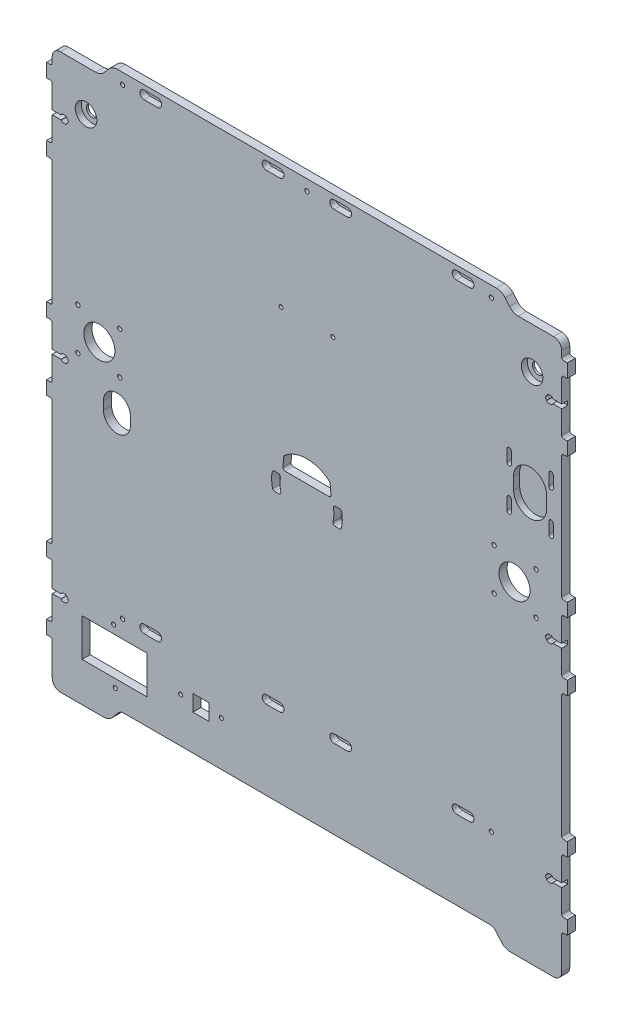
SolidWorks part; units mm, degrees
ref_plane "Alzado" through (0, 0, 0) normal (0, 0, 1) x (1, 0, 0)
ref_plane "Planta" through (0, 0, 0) normal (0, 1, 0) x (1, 0, 0)
ref_plane "Vista lateral" through (0, 0, 0) normal (1, 0, 0) x (0, 0, -1)
sketch "Croquis1" plane through (0, 0, 0) normal (0, 0, 1) x (1, 0, 0)
  line L0 (-10.6795, 26.7767) -> (-13.879, 26.7767)
  line L1 (-34.6047, 239.0104) -> (-34.6047, -170.9896) construction
  line L2 (-13.5151, 39.6941) -> (-10.3636, 39.6941)
  line L3 (-222.9547, 187.3104) -> (-34.6047, 187.3104) construction
  line L4 (-128.7797, 34.0104) -> (-128.7797, 187.3104) construction
  line L5 (-222.9547, 205.7604) -> (-222.9547, 168.8604)
  line L6 (-16.827, 45.3024) -> (-17.4546, 52.4766)
  line L7 (-50.8381, 43.6172) -> (-18.3712, 43.6172)
  line L8 (-51.7547, 52.4766) -> (-52.3823, 45.3024)
  line L9 (-227.1047, 167.3104) -> (-224.5047, 167.3104)
  line L10 (-58.5298, 26.7767) -> (-55.3303, 26.7767)
  line L11 (-55.6942, 39.6941) -> (-58.8457, 39.6941)
  line L12 (-227.1047, 157.3104) -> (-227.1047, 167.3104)
  line L13 (-224.5047, 157.3104) -> (-227.1047, 157.3104)
  line L14 (-224.5047, -89.2896) -> (-227.1047, -89.2896)
  line L15 (-227.1047, -89.2896) -> (-227.1047, -99.2896)
  line L16 (-34.6047, 34.0104) -> (-222.9547, 34.0104) construction
  line L17 (-227.1047, -99.2896) -> (-224.5047, -99.2896)
  line L18 (-18.3712, 43.6172) -> (-50.8381, 43.6172)
  line L19 (-17.4546, 52.4766) -> (-16.827, 45.3024)
  line L20 (-55.3303, 26.7767) -> (-58.5298, 26.7767)
  line L21 (-227.1047, -139.2896) -> (-224.5047, -139.2896)
  line L22 (-227.1047, -149.2896) -> (-227.1047, -139.2896)
  line L23 (-224.5047, -149.2896) -> (-227.1047, -149.2896)
  line L25 (-222.9547, -137.7396) -> (-222.9547, -100.8396)
  line L32 (147.7453, -180.9896) -> (115.7453, -180.9896)
  line L36 (100.8221, -170.9896) -> (-170.0314, -170.9896)
  line L37 (-210.4105, 34.0104) -> (-223.8121, 34.0104) construction
  line L38 (-222.9547, 15.5604) -> (-222.9547, 52.4604)
  line L42 (153.7453, 2.4611) -> (153.7453, -87.7396)
  line L43 (-227.1047, 14.0104) -> (-224.5047, 14.0104)
  line L44 (-227.1047, 4.0104) -> (-227.1047, 14.0104)
  line L45 (-224.5047, 4.0104) -> (-227.1047, 4.0104)
  line L46 (-224.5047, 64.0104) -> (-227.1047, 64.0104)
  line L47 (-227.1047, 64.0104) -> (-227.1047, 54.0104)
  line L48 (-227.1047, 54.0104) -> (-224.5047, 54.0104)
  line L49 (-185.1047, 15.6104) -> (-185.1047, 21.6104)
  line L50 (-165.1047, 21.6104) -> (-165.1047, 15.6104)
  line L51 (-204.0289, 73.6104) -> (-173.0289, 73.6104) construction
  line L52 (-200.9547, -123.9896) -> (-152.9547, -123.9896)
  line L53 (113.2425, 131.6103) -> (113.2419, 140.1103)
  line L54 (116.5488, 140.1105) -> (116.5494, 131.6105)
  line L55 (144.2425, 131.6103) -> (144.2419, 140.1103)
  line L56 (147.5488, 140.1105) -> (147.5494, 131.6105)
  line L57 (130.2626, 109.7644) -> (130.2626, 118.2644) construction
  line L58 (107.5281, 109.7644) -> (107.5281, 118.2644) construction
  line L59 (116.5488, 140.1105) -> (147.5488, 140.1105) construction
  line L60 (113.2425, 100.6103) -> (113.2419, 109.1103)
  line L61 (116.5488, 109.1105) -> (116.5494, 100.6105)
  line L62 (144.2425, 100.6103) -> (144.2419, 109.1103)
  line L63 (-34.6047, 34.0104) -> (153.7453, 34.0104) construction
  line L64 (-200.9547, -123.9896) -> (-200.9547, -151.9896)
  line L65 (-200.9547, -151.9896) -> (-152.9547, -151.9896)
  line L66 (-152.9547, -123.9896) -> (-152.9547, -151.9896)
  line L67 (-118.9547, -132.8214) -> (-106.9547, -132.8214)
  line L68 (-118.9547, -132.8214) -> (-118.9547, -144.8214)
  line L69 (109.234, -177.9533) -> (105.0418, -172.9573)
  line L73 (-222.9547, 155.7604) -> (-222.9547, 65.5604)
  line L74 (-222.9547, 2.4611) -> (-222.9547, -87.7396)
  line L75 (-222.9547, -150.8396) -> (-222.9547, -174.9896)
  line L77 (153.7453, -150.8396) -> (153.7453, -174.9896)
  line L81 (157.8953, -99.2896) -> (155.2953, -99.2896)
  line L82 (157.8953, -89.2896) -> (157.8953, -99.2896)
  line L83 (155.2953, -89.2896) -> (157.8953, -89.2896)
  line L84 (155.2953, -149.2896) -> (157.8953, -149.2896)
  line L85 (157.8953, -149.2896) -> (157.8953, -139.2896)
  line L86 (157.8953, -139.2896) -> (155.2953, -139.2896)
  line L87 (153.7453, -137.7396) -> (153.7453, -100.8396)
  line L91 (155.2953, 4.0104) -> (157.8953, 4.0104)
  line L92 (157.8953, 4.0104) -> (157.8953, 14.0104)
  line L93 (157.8953, 14.0104) -> (155.2953, 14.0104)
  line L94 (-118.9547, -144.8214) -> (-106.9547, -144.8214)
  line L95 (-106.9547, -132.8214) -> (-106.9547, -144.8214)
  line L96 (-118.9547, -132.8214) -> (-106.9547, -144.8214) construction
  line L97 (-118.9547, -144.8214) -> (-106.9547, -132.8214) construction
  line L98 (-204.0289, 73.6104) -> (-204.0289, 42.6104) construction
  line L99 (134.8196, 73.6104) -> (134.8196, 42.6104) construction
  line L100 (134.8196, 73.6104) -> (103.8196, 73.6104) construction
  line L101 (118.8953, 57.6104) -> (118.8953, 118.2644) construction
  line L102 (147.5488, 109.1105) -> (147.5494, 100.6105)
  line L103 (153.7453, 15.5604) -> (153.7453, 52.4604)
  line L104 (157.8953, 54.0104) -> (155.2953, 54.0104)
  line L105 (157.8953, 64.0104) -> (157.8953, 54.0104)
  line L106 (155.2953, 64.0104) -> (157.8953, 64.0104)
  line L107 (153.7453, 155.7604) -> (153.7453, 65.5604)
  line L108 (155.2953, 157.3104) -> (157.8953, 157.3104)
  line L109 (157.8953, 157.3104) -> (157.8953, 167.3104)
  line L110 (157.8953, 167.3104) -> (155.2953, 167.3104)
  line L115 (153.7453, 205.7604) -> (153.7453, 168.8604)
  line L116 (157.8953, 207.3104) -> (155.2953, 207.3104)
  line L117 (157.8953, 217.3104) -> (157.8953, 207.3104)
  line L118 (155.2953, 217.3104) -> (157.8953, 217.3104)
  line L119 (153.7453, 223.1104) -> (153.7453, 218.8604)
  line L120 (121.7453, 229.1104) -> (147.7453, 229.1104)
  line L121 (112.0224, 235.9741) -> (115.234, 232.1467)
  line L131 (105.511, 239.0104) -> (-174.7203, 239.0104)
  line L132 (-181.2317, 235.9741) -> (-184.4433, 232.1467)
  line L133 (-190.9547, 229.1104) -> (-216.9547, 229.1104)
  line L134 (-222.9547, 223.1104) -> (-222.9547, 218.8604)
  line L135 (-224.5047, 217.3104) -> (-227.1047, 217.3104)
  line L136 (-227.1047, 217.3104) -> (-227.1047, 207.3104)
  line L137 (-227.1047, 207.3104) -> (-224.5047, 207.3104)
  line L142 (-216.9547, -180.9896) -> (-184.9547, -180.9896)
  line L143 (-178.4433, -177.9533) -> (-174.2511, -172.9573)
  line L145 (-222.9547, 110.6604) -> (-34.6047, 110.6604) construction
  arc A0 (-8.8356, 38.4045) -> (-9.1714, 27.9685) centre (-34.6047, 34.0104) cw
  arc A1 (-9.1714, 27.9685) -> (-10.6795, 26.7767) centre (-10.6795, 28.3268) cw
  arc A2 (-222.9547, 168.8604) -> (-224.5047, 167.3104) centre (-224.5047, 168.8604) cw
  arc A3 (-224.5047, 157.3104) -> (-222.9547, 155.7604) centre (-224.5047, 155.7604) cw
  arc A4 (-13.879, 26.7767) -> (-15.3739, 28.7367) centre (-13.879, 28.3268) cw
  arc A5 (-15.0363, 37.8458) -> (-15.3739, 28.7367) centre (-34.6047, 34.0104) cw
  arc A6 (-15.0363, 37.8458) -> (-13.5151, 39.6941) centre (-13.5151, 38.144) cw
  arc A7 (-224.5047, -89.2896) -> (-222.9547, -87.7396) centre (-224.5047, -87.7396) ccw
  arc A8 (-222.9547, -100.8396) -> (-224.5047, -99.2896) centre (-224.5047, -100.8396) ccw
  arc A9 (-222.9547, -137.7396) -> (-224.5047, -139.2896) centre (-224.5047, -137.7396) cw
  arc A10 (-18.3712, 43.6172) -> (-16.827, 45.3024) centre (-18.3712, 45.1673) ccw
  arc A11 (-52.3823, 45.3024) -> (-50.8381, 43.6172) centre (-50.8381, 45.1673) ccw
  arc A12 (-51.2153, 53.5218) -> (-51.7547, 52.4766) centre (-50.2105, 52.3415) ccw
  arc A13 (-17.994, 53.5218) -> (-51.2153, 53.5218) centre (-34.6047, 34.0104) ccw
  arc A14 (-17.4546, 52.4766) -> (-17.994, 53.5218) centre (-18.9988, 52.3415) ccw
  arc A15 (-224.5047, -149.2896) -> (-222.9547, -150.8396) centre (-224.5047, -150.8396) cw
  arc A16 (-10.3636, 39.6941) -> (-8.8356, 38.4045) centre (-10.3636, 38.144) cw
  arc A18 (-222.9547, -174.9896) -> (-216.9547, -180.9896) centre (-216.9547, -174.9896) ccw
  arc A22 (-55.3303, 26.7767) -> (-53.8354, 28.7367) centre (-55.3303, 28.3268) ccw
  arc A23 (-60.0379, 27.9685) -> (-58.5298, 26.7767) centre (-58.5298, 28.3268) ccw
  arc A24 (-60.3738, 38.4045) -> (-60.0379, 27.9685) centre (-34.6047, 34.0104) ccw
  arc A25 (-58.8457, 39.6941) -> (-60.3738, 38.4045) centre (-58.8457, 38.144) ccw
  arc A26 (-54.173, 37.8458) -> (-55.6942, 39.6941) centre (-55.6942, 38.144) ccw
  arc A27 (-54.173, 37.8458) -> (-53.8354, 28.7367) centre (-34.6047, 34.0104) ccw
  arc A28 (-222.9547, 15.5604) -> (-224.5047, 14.0104) centre (-224.5047, 15.5604) cw
  arc A29 (-224.5047, 4.0104) -> (-222.9547, 2.4604) centre (-224.5047, 2.4604) cw
  arc A30 (-224.5047, 64.0104) -> (-222.9547, 65.5604) centre (-224.5047, 65.5604) ccw
  arc A31 (-222.9547, 52.4604) -> (-224.5047, 54.0104) centre (-224.5047, 52.4604) ccw
  arc A40 (100.8221, -170.9896) -> (105.0418, -172.9573) centre (100.8221, -176.498) cw
  arc A41 (115.7453, -180.9896) -> (109.234, -177.9533) centre (115.7453, -172.4896) cw
  arc A42 (153.7453, -174.9896) -> (147.7453, -180.9896) centre (147.7453, -174.9896) cw
  arc A45 (153.7453, -100.8396) -> (155.2953, -99.2896) centre (155.2953, -100.8396) cw
  arc A46 (-17.994, 53.5218) -> (-51.2153, 53.5218) centre (-34.6047, 34.0104) ccw
  arc A47 (-17.4546, 52.4766) -> (-17.994, 53.5218) centre (-18.9988, 52.3415) ccw
  arc A48 (-18.3712, 43.6172) -> (-16.827, 45.3024) centre (-18.3712, 45.1673) ccw
  arc A49 (-52.3823, 45.3024) -> (-50.8381, 43.6172) centre (-50.8381, 45.1673) ccw
  arc A50 (-51.2153, 53.5218) -> (-51.7547, 52.4766) centre (-50.2105, 52.3415) ccw
  arc A51 (-58.8457, 39.6941) -> (-60.3738, 38.4045) centre (-58.8457, 38.144) ccw
  arc A52 (-60.3738, 38.4045) -> (-60.0379, 27.9685) centre (-34.6047, 34.0104) ccw
  arc A53 (-60.0379, 27.9685) -> (-58.5298, 26.7767) centre (-58.5298, 28.3268) ccw
  arc A54 (-55.3303, 26.7767) -> (-53.8354, 28.7367) centre (-55.3303, 28.3268) ccw
  arc A55 (-54.173, 37.8458) -> (-53.8354, 28.7367) centre (-34.6047, 34.0104) ccw
  arc A56 (-54.173, 37.8458) -> (-55.6942, 39.6941) centre (-55.6942, 38.144) ccw
  arc A62 (155.2953, -89.2896) -> (153.7453, -87.7396) centre (155.2953, -87.7396) cw
  arc A63 (155.2953, -149.2896) -> (153.7453, -150.8396) centre (155.2953, -150.8396) ccw
  arc A64 (153.7453, -137.7396) -> (155.2953, -139.2896) centre (155.2953, -137.7396) ccw
  arc A68 (155.2953, 4.0104) -> (153.7453, 2.4604) centre (155.2953, 2.4604) ccw
  arc A69 (153.7453, 15.5604) -> (155.2953, 14.0104) centre (155.2953, 15.5604) ccw
  circle A70 centre (101.7453, 231.0104) radius 1.6
  circle A71 centre (-34.6047, 231.0104) radius 1.6
  circle A73 centre (101.7453, -110.9896) radius 1.6
  circle A74 centre (-177.5547, -117.9896) radius 1.5
  arc A75 (153.7453, 52.4604) -> (155.2953, 54.0104) centre (155.2953, 52.4604) cw
  arc A76 (155.2953, 64.0104) -> (153.7453, 65.5604) centre (155.2953, 65.5604) cw
  arc A77 (155.2953, 157.3104) -> (153.7453, 155.7604) centre (155.2953, 155.7604) ccw
  arc A78 (153.7453, 168.8604) -> (155.2953, 167.3104) centre (155.2953, 168.8604) ccw
  arc A83 (153.7453, 205.7604) -> (155.2953, 207.3104) centre (155.2953, 205.7604) cw
  arc A84 (155.2953, 217.3104) -> (153.7453, 218.8604) centre (155.2953, 218.8604) cw
  arc A85 (147.7453, 229.1104) -> (153.7453, 223.1104) centre (147.7453, 223.1104) cw
  arc A86 (121.7453, 229.1104) -> (115.234, 232.1467) centre (121.7453, 237.6104) cw
  arc A87 (105.511, 239.0104) -> (112.0224, 235.9741) centre (105.511, 230.5104) cw
  circle A88 centre (-176.3547, -157.9896) radius 1.5
  arc A89 (-174.7203, 239.0104) -> (-181.2317, 235.9741) centre (-174.7203, 230.5104) ccw
  arc A90 (-190.9547, 229.1104) -> (-184.4433, 232.1467) centre (-190.9547, 237.6104) ccw
  arc A91 (-216.9547, 229.1104) -> (-222.9547, 223.1104) centre (-216.9547, 223.1104) ccw
  arc A92 (-224.5047, 217.3104) -> (-222.9547, 218.8604) centre (-224.5047, 218.8604) ccw
  arc A93 (-222.9547, 205.7604) -> (-224.5047, 207.3104) centre (-224.5047, 205.7604) ccw
  arc A97 (-184.9547, -180.9896) -> (-178.4433, -177.9533) centre (-184.9547, -172.4896) ccw
  arc A98 (-170.0314, -170.9896) -> (-174.2511, -172.9573) centre (-170.0314, -176.498) ccw
  circle A99 centre (-188.1047, 57.6104) radius 11.5
  circle A100 centre (-204.0289, 73.6104) radius 1.6
  circle A101 centre (-173.0289, 73.6104) radius 1.6
  circle A102 centre (-204.0289, 42.6104) radius 1.6
  circle A103 centre (-173.0289, 42.6104) radius 1.6
  arc A104 (-165.1047, 21.6104) -> (-185.1047, 21.6104) centre (-175.1047, 21.6104) ccw
  arc A105 (-185.1047, 15.6104) -> (-165.1047, 15.6104) centre (-175.1047, 15.6104) ccw
  circle A106 centre (-127.9547, -137.9896) radius 1.5
  circle A107 centre (-197.9547, 198.6104) radius 4.25
  circle A108 centre (-170.9547, 231.0104) radius 1.6
  circle A109 centre (-97.9547, -137.9896) radius 1.5
  circle A110 centre (103.8196, 42.6104) radius 1.6
  circle A111 centre (134.8196, 42.6104) radius 1.6
  circle A112 centre (103.8196, 73.6104) radius 1.6
  circle A113 centre (131.8953, 198.6104) radius 4.25
  arc A114 (116.5488, 140.1105) -> (113.2419, 140.1103) centre (114.8953, 140.1104) ccw
  arc A115 (113.2425, 131.6103) -> (116.5494, 131.6105) centre (114.8959, 131.6104) ccw
  arc A116 (147.5488, 140.1105) -> (144.2419, 140.1103) centre (145.8953, 140.1104) ccw
  arc A117 (144.2425, 131.6103) -> (147.5494, 131.6105) centre (145.8959, 131.6104) ccw
  arc A118 (130.2626, 118.2644) -> (107.5281, 118.2644) centre (118.8953, 118.2644) ccw construction
  arc A119 (107.5281, 109.7644) -> (130.2626, 109.7644) centre (118.8953, 109.7644) ccw construction
  arc A120 (116.5488, 109.1105) -> (113.2419, 109.1103) centre (114.8953, 109.1104) ccw
  arc A121 (113.2425, 100.6103) -> (116.5494, 100.6105) centre (114.8959, 100.6104) ccw
  arc A122 (147.5488, 109.1105) -> (144.2419, 109.1103) centre (145.8953, 109.1104) ccw
  arc A123 (144.2425, 100.6103) -> (147.5494, 100.6105) centre (145.8959, 100.6104) ccw
  circle A124 centre (134.8196, 73.6104) radius 1.6
  circle A125 centre (118.8953, 57.6104) radius 11.5
  circle A133 centre (-170.9547, -110.9896) radius 1.6
  point P250 (-112.9547, -138.8214)
  dimension "D1" = 8.5
  dimension "D3" = 8.5
  dimension "D4" = 6
  dimension "D8" = 1.55
  dimension "D11" = 1.55
  dimension "D12" = 25
  dimension "D14" = 8.5
  dimension "D15" = 25.6244
  dimension "D21" = 6
  dimension "D23" = 40
  dimension "D26" = 8
  dimension "D27" = 32
  dimension "D29" = 3.2
  dimension "D30" = 8.5
  dimension "D7" = 3.2
  dimension "D31" = 48
  dimension "D38" = 6
  dimension "D39" = 6
  dimension "D40" = 25
  dimension "D45" = 9
  dimension "D47" = 3.2
  dimension "D54" = 23
  dimension "D57" = 10
  dimension "D58" = 10
  dimension "D63" = 89
  dimension "D64" = 8.5
  dimension "D65" = 1.6534
  dimension "D66" = 1.6534
  dimension "D20" = 1.5501
  dimension "D67" = 1.5501
  dimension "D71" = 1.5501
  dimension "D72" = 1.5501
  dimension "D75" = 1.5501
  dimension "D77" = 1.5501
  dimension "D78" = 26.1411
  dimension "D79" = 1.5501
  dimension "D81" = 1.5501
  dimension "D82" = 19.9407
  dimension "D87" = 1.55
  dimension "D88" = 1.55
  dimension "D2" = 50
  dimension "D5" = 8
  dimension "D6" = 52
  dimension "D9" = 10
  dimension "D10" = 2.6
  dimension "D13" = 40.4
  dimension "D16" = 21.85
  dimension "D17" = 11.8
  dimension "D18" = 32
  dimension "D19" = 15.9
  dimension "D22" = 7.1742
  dimension "D24" = 40.4
  dimension "D25" = 38.85
  dimension "D28" = 52
  dimension "D32" = 10
  dimension "D62" = 7.1682
  dimension "D89" = 22.5
  dimension "D33" = 6.5218
  dimension "D34" = 50
  dimension "D35" = 28
  dimension "D36" = 13
  dimension "D37" = 22
  dimension "D41" = 14
  dimension "D42" = 12
  dimension "D43" = 12
  dimension "D44" = 9
  dimension "D46" = 14
  dimension "D48" = 2
  dimension "D49" = 31
  dimension "D51" = 31
  dimension "D52" = 16
  dimension "D53" = 36
  dimension "D55" = 141
  dimension "D56" = 39
  dimension "D59" = 6
  dimension "D60" = 6
  dimension "D61" = 52
  dimension "D68" = 2
  dimension "D69" = 31
  dimension "D73" = 7.1742
  dimension "D74" = 32.467
  dimension "D76" = 3.1515
  dimension "D80" = 3.1995
  dimension "D83" = 24.2411
  dimension "D84" = 23.9251
  dimension "D85" = 10
  dimension "D86" = 2.6
  dimension "D50" = 2
  dimension "D70" = 2
extrude "Saliente-Extruir1" add sketch "Croquis1" along normal blind 6
sketch "Croquis10" plane through (0, 0, 6) normal (0, 0, 1) x (1, 0, 0)
  line L0 (142.672, 116.1611) -> (142.672, 124.6104)
  line L1 (118.2177, 116.019) -> (118.1195, 124.4678)
  line L2 (114.8953, 140.1104) -> (145.8953, 109.1104) construction
  line L3 (-216.4544, 188.8604) -> (-222.9547, 188.8604)
  line L4 (-209.8753, 187.3104) -> (-223.8121, 187.3104) construction
  line L5 (-214.9445, 190.0604) -> (-213.3945, 190.0604)
  line L6 (-211.8813, 188.8465) -> (-211.8813, 188.6773)
  line L7 (-222.9547, 34.0104) -> (153.7453, 34.0104) construction
  line L8 (-211.8813, 185.9436) -> (-211.8813, 185.7743)
  line L9 (-214.9445, 184.5604) -> (-213.3945, 184.5604)
  line L10 (-222.9547, 188.8604) -> (-222.9547, 185.7604)
  line L11 (-34.6047, 239.0104) -> (-34.6047, -170.9896) construction
  line L12 (105.511, 239.0104) -> (-174.7203, 239.0104) construction
  line L13 (100.8221, -170.9896) -> (-170.0314, -170.9896) construction
  line L14 (-222.9547, 15.5604) -> (-222.9547, 52.4604) construction
  line L15 (-216.4544, 185.7604) -> (-222.9547, 185.7604)
  line L16 (-222.9547, 110.6604) -> (-34.6047, 110.6604) construction
  line L17 (-222.9547, 155.7604) -> (-222.9547, 65.5604) construction
  line L18 (-209.8753, 34.0104) -> (-223.8121, 34.0104) construction
  line L19 (-216.4544, 35.5604) -> (-222.9547, 35.5604)
  line L20 (-222.9547, 32.4604) -> (-222.9547, 35.5604)
  line L21 (-214.9445, 36.7604) -> (-213.3945, 36.7604)
  line L22 (-211.8813, 35.3773) -> (-211.8813, 35.5465)
  line L23 (-211.8813, 32.4743) -> (-211.8813, 32.6436)
  line L24 (-214.9445, 31.2604) -> (-213.3945, 31.2604)
  line L25 (-216.4544, 32.4604) -> (-222.9547, 32.4604)
  line L26 (-209.8753, -119.2896) -> (-223.8121, -119.2896) construction
  line L27 (-216.4544, -117.7396) -> (-222.9547, -117.7396)
  line L28 (-222.9547, -120.8396) -> (-222.9547, -117.7396)
  line L29 (-214.9445, -116.5396) -> (-213.3945, -116.5396)
  line L30 (-211.8813, -117.9227) -> (-211.8813, -117.7535)
  line L31 (-211.8813, -120.8257) -> (-211.8813, -120.6564)
  line L32 (-214.9445, -122.0396) -> (-213.3945, -122.0396)
  line L33 (-216.4544, -120.8396) -> (-222.9547, -120.8396)
  line L34 (140.666, -119.2896) -> (154.6028, -119.2896) construction
  line L35 (147.2451, -120.8396) -> (153.7453, -120.8396)
  line L36 (145.7352, -122.0396) -> (144.1852, -122.0396)
  line L37 (142.672, -120.8257) -> (142.672, -120.6564)
  line L38 (142.672, -117.9227) -> (142.672, -117.7535)
  line L39 (145.7352, -116.5396) -> (144.1852, -116.5396)
  line L40 (153.7453, -120.8396) -> (153.7453, -117.7396)
  line L41 (147.2451, -117.7396) -> (153.7453, -117.7396)
  line L42 (140.666, 34.0104) -> (154.6028, 34.0104) construction
  line L43 (147.2451, 32.4604) -> (153.7453, 32.4604)
  line L44 (145.7352, 31.2604) -> (144.1852, 31.2604)
  line L45 (142.672, 32.4743) -> (142.672, 32.6436)
  line L46 (142.672, 35.3773) -> (142.672, 35.5465)
  line L47 (145.7352, 36.7604) -> (144.1852, 36.7604)
  line L48 (153.7453, 32.4604) -> (153.7453, 35.5604)
  line L49 (147.2451, 35.5604) -> (153.7453, 35.5604)
  line L50 (140.666, 187.3104) -> (154.6028, 187.3104) construction
  line L51 (147.2451, 185.7604) -> (153.7453, 185.7604)
  line L52 (153.7453, 188.8604) -> (153.7453, 185.7604)
  line L53 (145.7352, 184.5604) -> (144.1852, 184.5604)
  line L54 (142.672, 185.9436) -> (142.672, 185.7743)
  line L55 (142.672, 188.8465) -> (142.672, 188.6773)
  line L56 (145.7352, 190.0604) -> (144.1852, 190.0604)
  line L57 (147.2451, 188.8604) -> (153.7453, 188.8604)
  line L58 (-64.6047, 235.6104) -> (-54.6047, 235.6104)
  line L59 (-64.6047, 229.4104) -> (-54.6047, 229.4104)
  line L60 (153.7453, 15.5604) -> (153.7453, 52.4604) construction
  line L61 (-155.1047, 235.6104) -> (-145.1047, 235.6104)
  line L62 (-155.1047, 229.4104) -> (-145.1047, 229.4104)
  line L63 (-54.6047, 229.4104) -> (-145.1047, 229.4104) construction
  line L64 (-4.6047, 229.4104) -> (-14.6047, 229.4104)
  line L65 (-4.6047, 235.6104) -> (-14.6047, 235.6104)
  line L66 (85.8953, 235.6104) -> (75.8953, 235.6104)
  line L67 (85.8953, 229.4104) -> (75.8953, 229.4104)
  line L68 (-64.6047, -112.5896) -> (-54.6047, -112.5896)
  line L69 (-64.6047, -106.3896) -> (-54.6047, -106.3896)
  line L70 (-155.1047, -106.3896) -> (-145.1047, -106.3896)
  line L71 (-155.1047, -112.5896) -> (-145.1047, -112.5896)
  line L72 (-4.6047, -112.5896) -> (-14.6047, -112.5896)
  line L73 (-4.6047, -106.3896) -> (-14.6047, -106.3896)
  line L74 (85.8953, -106.3896) -> (75.8953, -106.3896)
  line L75 (85.8953, -112.5896) -> (75.8953, -112.5896)
  line L76 (-54.6047, 229.4104) -> (-54.6047, -112.5896) construction
  line L77 (145.8953, 140.1104) -> (114.8953, 109.1104) construction
  line L78 (-190.9547, 229.1104) -> (-216.9547, 229.1104) construction
  line L79 (-227.1047, 64.0104) -> (-227.1047, 54.0104) construction
  line L80 (-227.1047, 59.0104) -> (157.8953, 59.0104) construction
  line L81 (157.8953, 64.0104) -> (157.8953, 54.0104) construction
  line L82 (-222.9547, 205.7604) -> (-222.9547, 168.8604) construction
  arc A0 (142.672, 124.6104) -> (118.1195, 124.4678) centre (130.3953, 124.6104) ccw
  arc A1 (118.2177, 116.019) -> (142.672, 116.1611) centre (130.4444, 116.1611) ccw
  arc A2 (-214.9445, 36.7604) -> (-216.4544, 35.5604) centre (-214.9445, 35.2104) ccw
  circle A3 centre (131.8953, 198.6104) radius 4.25
  arc A4 (-211.8813, 32.4743) -> (-213.3945, 31.2604) centre (-213.3945, 32.8104) cw
  arc A5 (-214.9445, 31.2604) -> (-216.4544, 32.4604) centre (-214.9445, 32.8104) cw
  arc A6 (-211.8813, 35.5465) -> (-213.3945, 36.7604) centre (-213.3945, 35.2104) ccw
  arc A7 (-211.8813, 35.3773) -> (-211.8813, 32.6436) centre (-212.6118, 34.0104) cw
  arc A8 (-211.8813, 185.9436) -> (-211.8813, 188.6773) centre (-212.6118, 187.3104) ccw
  arc A9 (-214.9445, -116.5396) -> (-216.4544, -117.7396) centre (-214.9445, -118.0896) ccw
  arc A10 (-211.8813, -120.8257) -> (-213.3945, -122.0396) centre (-213.3945, -120.4896) cw
  arc A11 (-214.9445, -122.0396) -> (-216.4544, -120.8396) centre (-214.9445, -120.4896) cw
  arc A12 (-211.8813, -117.7535) -> (-213.3945, -116.5396) centre (-213.3945, -118.0896) ccw
  arc A13 (-211.8813, -117.9227) -> (-211.8813, -120.6564) centre (-212.6118, -119.2896) cw
  arc A14 (142.672, -117.9227) -> (142.672, -120.6564) centre (143.4025, -119.2896) ccw
  arc A15 (142.672, -117.7535) -> (144.1852, -116.5396) centre (144.1852, -118.0896) cw
  arc A16 (145.7352, -122.0396) -> (147.2451, -120.8396) centre (145.7352, -120.4896) ccw
  arc A17 (142.672, -120.8257) -> (144.1852, -122.0396) centre (144.1852, -120.4896) ccw
  arc A18 (145.7352, -116.5396) -> (147.2451, -117.7396) centre (145.7352, -118.0896) cw
  arc A19 (142.672, 35.3773) -> (142.672, 32.6436) centre (143.4025, 34.0104) ccw
  arc A20 (142.672, 35.5465) -> (144.1852, 36.7604) centre (144.1852, 35.2104) cw
  arc A21 (145.7352, 31.2604) -> (147.2451, 32.4604) centre (145.7352, 32.8104) ccw
  arc A22 (142.672, 32.4743) -> (144.1852, 31.2604) centre (144.1852, 32.8104) ccw
  arc A23 (145.7352, 36.7604) -> (147.2451, 35.5604) centre (145.7352, 35.2104) cw
  arc A24 (145.7352, 184.5604) -> (147.2451, 185.7604) centre (145.7352, 186.1104) ccw
  arc A25 (142.672, 188.8465) -> (144.1852, 190.0604) centre (144.1852, 188.5104) cw
  arc A26 (145.7352, 190.0604) -> (147.2451, 188.8604) centre (145.7352, 188.5104) cw
  arc A27 (142.672, 185.7743) -> (144.1852, 184.5604) centre (144.1852, 186.1104) ccw
  arc A28 (142.672, 185.9436) -> (142.672, 188.6773) centre (143.4025, 187.3104) cw
  arc A29 (-54.6047, 229.4104) -> (-54.6047, 235.6104) centre (-54.6047, 232.5104) ccw
  arc A30 (-64.6047, 235.6104) -> (-64.6047, 229.4104) centre (-64.6047, 232.5104) ccw
  arc A31 (-145.1047, 229.4104) -> (-145.1047, 235.6104) centre (-145.1047, 232.5104) ccw
  arc A32 (-155.1047, 235.6104) -> (-155.1047, 229.4104) centre (-155.1047, 232.5104) ccw
  arc A33 (-14.6047, 229.4104) -> (-14.6047, 235.6104) centre (-14.6047, 232.5104) cw
  arc A34 (-4.6047, 235.6104) -> (-4.6047, 229.4104) centre (-4.6047, 232.5104) cw
  arc A35 (75.8953, 229.4104) -> (75.8953, 235.6104) centre (75.8953, 232.5104) cw
  arc A36 (85.8953, 235.6104) -> (85.8953, 229.4104) centre (85.8953, 232.5104) cw
  arc A37 (-54.6047, -112.5896) -> (-54.6047, -106.3896) centre (-54.6047, -109.4896) ccw
  arc A38 (-64.6047, -106.3896) -> (-64.6047, -112.5896) centre (-64.6047, -109.4896) ccw
  arc A39 (-145.1047, -112.5896) -> (-145.1047, -106.3896) centre (-145.1047, -109.4896) ccw
  arc A40 (-155.1047, -106.3896) -> (-155.1047, -112.5896) centre (-155.1047, -109.4896) ccw
  arc A41 (-14.6047, -112.5896) -> (-14.6047, -106.3896) centre (-14.6047, -109.4896) cw
  arc A42 (-4.6047, -106.3896) -> (-4.6047, -112.5896) centre (-4.6047, -109.4896) cw
  arc A43 (75.8953, -112.5896) -> (75.8953, -106.3896) centre (75.8953, -109.4896) cw
  arc A44 (85.8953, -106.3896) -> (85.8953, -112.5896) centre (85.8953, -109.4896) cw
  circle A45 centre (-197.9547, 198.6104) radius 8
  circle A46 centre (131.8953, 198.6104) radius 8
  circle A47 centre (131.8953, 198.6104) radius 4.25 construction
  arc A63 (-211.8813, 185.7743) -> (-213.3945, 184.5604) centre (-213.3945, 186.1104) cw
  arc A65 (-214.9445, 190.0604) -> (-216.4544, 188.8604) centre (-214.9445, 188.5104) ccw
  arc A66 (-211.8813, 188.8465) -> (-213.3945, 190.0604) centre (-213.3945, 188.5104) ccw
  arc A67 (-214.9445, 184.5604) -> (-216.4544, 185.7604) centre (-214.9445, 186.1104) cw
  point P203 (130.3953, 124.6104)
  dimension "D4" = 6.2
  dimension "D5" = 10
  dimension "D12" = 6.5002
  dimension "D2" = 16
  dimension "D3" = 16
  dimension "D13" = 1.55
  dimension "D15" = 1.55
  dimension "D17" = 1.5498
  dimension "D6" = 20
  dimension "D7" = 6.5
  dimension "D10" = 15.85
  dimension "D14" = 1.55
  dimension "D16" = 0.1692
  dimension "D18" = 41.8
  dimension "D19" = 1.55
  dimension "D20" = 1.2
  dimension "D23" = 2.7365
  dimension "D24" = 1.3669
  dimension "D8" = 2
  dimension "D11" = 2
extrude "Cortar-Extruir4" cut sketch "Croquis10" against normal blind 4.5
chamfer "Chaflán1" distance 1.5 angle 45 17 edges at (-96.4547, -137.9896, 0) (-126.4547, -137.9896, 0) (-174.8547, -157.9896, 0) (-176.0547, -117.9896, 0) (-169.3547, -110.9896, 0) (103.3453, -110.9896, 0) (136.4196, 42.6104, 0) (105.4196, 42.6104, 0) (105.4196, 73.6104, 0) (136.4196, 73.6104, 0) (-202.4289, 42.6104, 0) (-171.4289, 42.6104, 0) (-171.4289, 73.6104, 0) (-202.4289, 73.6104, 0) (-169.3547, 231.0104, 0) (-33.0047, 231.0104, 0) (103.3453, 231.0104, 0)
sketch "Croquis11" plane through (0, 0, 6) normal (0, 0, 1) x (1, 0, 0)
  line L0 (114.8952, 141.7638) -> (-222.9547, 141.7638) construction
  line L1 (-222.9547, 155.7604) -> (-222.9547, 65.5604) construction
  line L2 (-34.6047, 231.0104) -> (-34.6047, -170.9896) construction
  line L3 (100.8221, -170.9896) -> (-170.0314, -170.9896) construction
  line L4 (-222.9547, 147.2638) -> (153.7453, 147.2638) construction
  line L5 (153.7453, 155.7604) -> (153.7453, 65.5604) construction
  circle A0 centre (-34.6047, 231.0104) radius 1.6 construction
  circle A1 centre (-34.6047, 231.0104) radius 1.6
  arc A2 (116.5488, 140.1105) -> (113.2419, 140.1103) centre (114.8953, 140.1104) ccw construction
  arc A3 (116.5488, 140.1105) -> (113.2419, 140.1103) centre (114.8953, 140.1104) ccw
  circle A4 centre (-53.7847, 147.2638) radius 1.5
  circle A5 centre (-15.4247, 147.2638) radius 1.5
  dimension "D2" = 19.18
  dimension "D3" = 19.18
  dimension "D1" = 5.5
  dimension "D4" = 38.36
extrude "Cortar-Extruir5" cut sketch "Croquis11" against normal blind 6 contours A4 | A5
equation "\"Ancho_panel\"= 385'Ancho del panel"
equation "\"Alto_panel\"= 420'Alto del panel izquierdo"
equation "\"Altura_base_taladros\"= 70'Alto taladros de la base eje Z"
equation "\"Altura_superior_taladros\"= 8mm'Distancia taladros a top"
equation "\"Distancia_vert_entre_horizontales_ensambles\"= \"Alto_panel\" - \"Altura_base_taladros\" - \"Altura_superior_taladros\"'Distancia vertical entre horizontales de ensambles"
equation "\"Latrales_separacion_barras_a_escalon_bajo\"= 12.5'Separación entre las barras y el escalón inferior de la parte superior"
equation "\"Espacio_tensor_correa_motor\"= 8.5mm'Espacio para mover el motor en vertical y tensar la correa"
